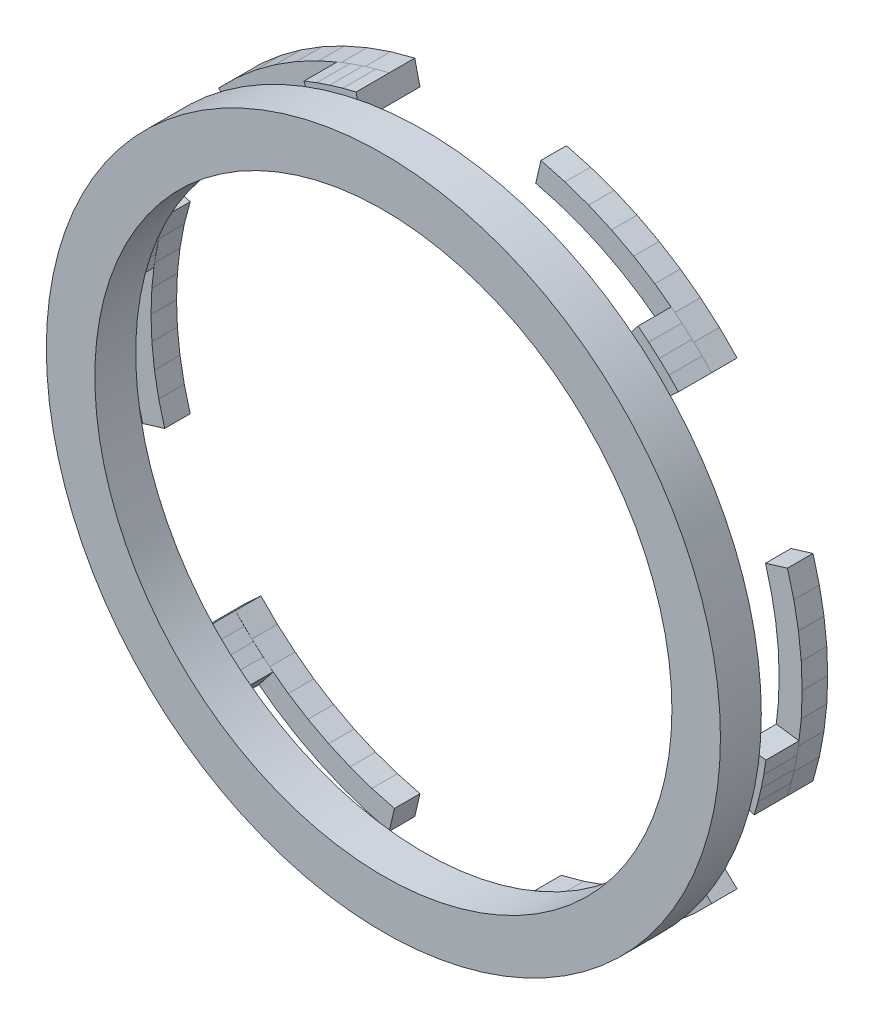
SolidWorks part; units mm, degrees
ref_plane "Front Plane" through (0, 0, 0) normal (0, 0, 1) x (1, 0, 0)
ref_plane "Top Plane" through (0, 0, 0) normal (0, 1, 0) x (1, 0, 0)
ref_plane "Right Plane" through (0, 0, 0) normal (1, 0, 0) x (0, 0, -1)
sketch "草圖1" plane through (0, 0, 0) normal (0, 0, 1) x (1, 0, 0)
  circle A0 centre (0, 0) radius 66
  circle A1 centre (0, 0) radius 56.5
extrude "填料-伸長1" add sketch "草圖1" along normal blind 8 from offset 13
sketch "草圖2" plane through (0, 0, 0) normal (0, 0, 1) x (1, 0, 0)
  line L0 (63.1161, -19.2965) -> (64.3726, -14.566)
  line L1 (64.3726, -14.566) -> (65.275, -9.7554)
  line L2 (65.275, -9.7554) -> (65.8185, -4.8912)
  line L3 (65.8185, -4.8912) -> (66, 0)
  line L4 (66, 0) -> (65.8185, 4.8912)
  line L5 (65.8185, 4.8912) -> (65.275, 9.7554)
  line L6 (65.275, 9.7554) -> (64.3726, 14.566)
  line L7 (64.3726, 14.566) -> (63.1161, 19.2965)
  line L8 (63.1161, 19.2965) -> (58.8127, 17.9809)
  line L9 (58.8127, 17.9809) -> (59.9836, 13.5729)
  line L10 (59.9836, 13.5729) -> (60.8245, 9.0903)
  line L11 (60.8245, 9.0903) -> (61.3309, 4.5577)
  line L12 (61.3309, 4.5577) -> (61.5, 0)
  line L13 (61.5, 0) -> (61.3309, -4.5577)
  line L14 (61.3309, -4.5577) -> (60.8245, -9.0903)
  line L15 (60.8245, -9.0903) -> (59.9836, -13.5729)
  line L16 (59.9836, -13.5729) -> (58.8127, -17.9809)
  line L17 (58.8127, -17.9809) -> (63.1161, -19.2965)
  line L18 (48.2693, 45.0119) -> (44.8008, 48.4653)
  line L19 (44.8008, 48.4653) -> (41.086, 51.6521)
  line L20 (41.086, 51.6521) -> (37.1451, 54.5549)
  line L21 (37.1451, 54.5549) -> (33, 57.1577)
  line L22 (33, 57.1577) -> (28.6734, 59.4461)
  line L23 (28.6734, 59.4461) -> (24.1891, 61.4076)
  line L24 (24.1891, 61.4076) -> (19.5717, 63.0313)
  line L25 (19.5717, 63.0313) -> (14.8468, 64.3084)
  line L26 (14.8468, 64.3084) -> (13.8345, 59.9238)
  line L27 (13.8345, 59.9238) -> (18.2373, 58.7337)
  line L28 (18.2373, 58.7337) -> (22.5398, 57.2207)
  line L29 (22.5398, 57.2207) -> (26.7184, 55.3929)
  line L30 (26.7184, 55.3929) -> (30.75, 53.2606)
  line L31 (30.75, 53.2606) -> (34.6125, 50.8353)
  line L32 (34.6125, 50.8353) -> (38.2847, 48.1304)
  line L33 (38.2847, 48.1304) -> (41.7462, 45.1608)
  line L34 (41.7462, 45.1608) -> (44.9783, 41.9429)
  line L35 (44.9783, 41.9429) -> (48.2693, 45.0119)
  line L36 (-14.8468, 64.3084) -> (-19.5717, 63.0313)
  line L37 (-19.5717, 63.0313) -> (-24.1891, 61.4076)
  line L38 (-24.1891, 61.4076) -> (-28.6734, 59.4461)
  line L39 (-28.6734, 59.4461) -> (-33, 57.1577)
  line L40 (-33, 57.1577) -> (-37.1451, 54.5549)
  line L41 (-37.1451, 54.5549) -> (-41.086, 51.6521)
  line L42 (-41.086, 51.6521) -> (-44.8008, 48.4653)
  line L43 (-44.8008, 48.4653) -> (-48.2693, 45.0119)
  line L44 (-48.2693, 45.0119) -> (-44.9783, 41.9429)
  line L45 (-44.9783, 41.9429) -> (-41.7462, 45.1608)
  line L46 (-41.7462, 45.1608) -> (-38.2847, 48.1304)
  line L47 (-38.2847, 48.1304) -> (-34.6125, 50.8353)
  line L48 (-34.6125, 50.8353) -> (-30.75, 53.2606)
  line L49 (-30.75, 53.2606) -> (-26.7184, 55.3929)
  line L50 (-26.7184, 55.3929) -> (-22.5398, 57.2207)
  line L51 (-22.5398, 57.2207) -> (-18.2373, 58.7337)
  line L52 (-18.2373, 58.7337) -> (-13.8345, 59.9238)
  line L53 (-13.8345, 59.9238) -> (-14.8468, 64.3084)
  line L54 (-63.1161, 19.2965) -> (-64.3726, 14.566)
  line L55 (-64.3726, 14.566) -> (-65.275, 9.7554)
  line L56 (-65.275, 9.7554) -> (-65.8185, 4.8912)
  line L57 (-65.8185, 4.8912) -> (-66, 0)
  line L58 (-66, 0) -> (-65.8185, -4.8912)
  line L59 (-65.8185, -4.8912) -> (-65.275, -9.7554)
  line L60 (-65.275, -9.7554) -> (-64.3726, -14.566)
  line L61 (-64.3726, -14.566) -> (-63.1161, -19.2965)
  line L62 (-63.1161, -19.2965) -> (-58.8127, -17.9809)
  line L63 (-58.8127, -17.9809) -> (-59.9836, -13.5729)
  line L64 (-59.9836, -13.5729) -> (-60.8245, -9.0903)
  line L65 (-60.8245, -9.0903) -> (-61.3309, -4.5577)
  line L66 (-61.3309, -4.5577) -> (-61.5, 0)
  line L67 (-61.5, 0) -> (-61.3309, 4.5577)
  line L68 (-61.3309, 4.5577) -> (-60.8245, 9.0903)
  line L69 (-60.8245, 9.0903) -> (-59.9836, 13.5729)
  line L70 (-59.9836, 13.5729) -> (-58.8127, 17.9809)
  line L71 (-58.8127, 17.9809) -> (-63.1161, 19.2965)
  line L72 (-48.2693, -45.0119) -> (-44.8008, -48.4653)
  line L73 (-44.8008, -48.4653) -> (-41.086, -51.6521)
  line L74 (-41.086, -51.6521) -> (-37.1451, -54.5549)
  line L75 (-37.1451, -54.5549) -> (-33, -57.1577)
  line L76 (-33, -57.1577) -> (-28.6734, -59.4461)
  line L77 (-28.6734, -59.4461) -> (-24.1891, -61.4076)
  line L78 (-24.1891, -61.4076) -> (-19.5717, -63.0313)
  line L79 (-19.5717, -63.0313) -> (-14.8468, -64.3084)
  line L80 (-14.8468, -64.3084) -> (-13.8345, -59.9238)
  line L81 (-13.8345, -59.9238) -> (-18.2373, -58.7337)
  line L82 (-18.2373, -58.7337) -> (-22.5398, -57.2207)
  line L83 (-22.5398, -57.2207) -> (-26.7184, -55.3929)
  line L84 (-26.7184, -55.3929) -> (-30.75, -53.2606)
  line L85 (-30.75, -53.2606) -> (-34.6125, -50.8353)
  line L86 (-34.6125, -50.8353) -> (-38.2847, -48.1304)
  line L87 (-38.2847, -48.1304) -> (-41.7462, -45.1608)
  line L88 (-41.7462, -45.1608) -> (-44.9783, -41.9429)
  line L89 (-44.9783, -41.9429) -> (-48.2693, -45.0119)
  line L90 (14.8468, -64.3084) -> (19.5717, -63.0313)
  line L91 (19.5717, -63.0313) -> (24.1891, -61.4076)
  line L92 (24.1891, -61.4076) -> (28.6734, -59.4461)
  line L93 (28.6734, -59.4461) -> (33, -57.1577)
  line L94 (33, -57.1577) -> (37.1451, -54.5549)
  line L95 (37.1451, -54.5549) -> (41.086, -51.6521)
  line L96 (41.086, -51.6521) -> (44.8008, -48.4653)
  line L97 (44.8008, -48.4653) -> (48.2693, -45.0119)
  line L98 (48.2693, -45.0119) -> (44.9783, -41.9429)
  line L99 (44.9783, -41.9429) -> (41.7462, -45.1608)
  line L100 (41.7462, -45.1608) -> (38.2847, -48.1304)
  line L101 (38.2847, -48.1304) -> (34.6125, -50.8353)
  line L102 (34.6125, -50.8353) -> (30.75, -53.2606)
  line L103 (30.75, -53.2606) -> (26.7184, -55.3929)
  line L104 (26.7184, -55.3929) -> (22.5398, -57.2207)
  line L105 (22.5398, -57.2207) -> (18.2373, -58.7337)
  line L106 (18.2373, -58.7337) -> (13.8345, -59.9238)
  line L107 (13.8345, -59.9238) -> (14.8468, -64.3084)
extrude "填料-伸長2" add sketch "草圖2" along normal blind 5
sketch "草圖3" plane through (0, 0, 0) normal (0, 0, 1) x (1, 0, 0)
  line L0 (63.1161, -19.2965) -> (63.847, -16.7202)
  line L1 (63.847, -16.7202) -> (64.4727, -14.1163)
  line L2 (64.4727, -14.1163) -> (64.9923, -11.4891)
  line L3 (64.9923, -11.4891) -> (65.4049, -8.8431)
  line L4 (65.4049, -8.8431) -> (60.9455, -8.2402)
  line L5 (60.9455, -8.2402) -> (60.561, -10.7058)
  line L6 (60.561, -10.7058) -> (60.0768, -13.1538)
  line L7 (60.0768, -13.1538) -> (59.4938, -15.5802)
  line L8 (59.4938, -15.5802) -> (58.8127, -17.9809)
  line L9 (58.8127, -17.9809) -> (63.1161, -19.2965)
  line L10 (48.2693, 45.0119) -> (46.4036, 46.933)
  line L11 (46.4036, 46.933) -> (44.4614, 48.7769)
  line L12 (44.4614, 48.7769) -> (42.446, 50.5404)
  line L13 (42.446, 50.5404) -> (40.3608, 52.2208)
  line L14 (40.3608, 52.2208) -> (37.6089, 48.6602)
  line L15 (37.6089, 48.6602) -> (39.552, 47.0945)
  line L16 (39.552, 47.0945) -> (41.4299, 45.4512)
  line L17 (41.4299, 45.4512) -> (43.2397, 43.733)
  line L18 (43.2397, 43.733) -> (44.9783, 41.9429)
  line L19 (44.9783, 41.9429) -> (48.2693, 45.0119)
  line L20 (-14.8468, 64.3084) -> (-17.4434, 63.6532)
  line L21 (-17.4434, 63.6532) -> (-20.0113, 62.8931)
  line L22 (-20.0113, 62.8931) -> (-22.5463, 62.0296)
  line L23 (-22.5463, 62.0296) -> (-25.0441, 61.0638)
  line L24 (-25.0441, 61.0638) -> (-23.3366, 56.9004)
  line L25 (-23.3366, 56.9004) -> (-21.009, 57.8003)
  line L26 (-21.009, 57.8003) -> (-18.6469, 58.605)
  line L27 (-18.6469, 58.605) -> (-16.2541, 59.3132)
  line L28 (-16.2541, 59.3132) -> (-13.8345, 59.9238)
  line L29 (-13.8345, 59.9238) -> (-14.8468, 64.3084)
  line L30 (-63.1161, 19.2965) -> (-63.847, 16.7202)
  line L31 (-63.847, 16.7202) -> (-64.4727, 14.1163)
  line L32 (-64.4727, 14.1163) -> (-64.9923, 11.4891)
  line L33 (-64.9923, 11.4891) -> (-65.4049, 8.8431)
  line L34 (-65.4049, 8.8431) -> (-60.9455, 8.2402)
  line L35 (-60.9455, 8.2402) -> (-60.561, 10.7058)
  line L36 (-60.561, 10.7058) -> (-60.0768, 13.1538)
  line L37 (-60.0768, 13.1538) -> (-59.4938, 15.5802)
  line L38 (-59.4938, 15.5802) -> (-58.8127, 17.9809)
  line L39 (-58.8127, 17.9809) -> (-63.1161, 19.2965)
  line L40 (-48.2693, -45.0119) -> (-46.4036, -46.933)
  line L41 (-46.4036, -46.933) -> (-44.4614, -48.7769)
  line L42 (-44.4614, -48.7769) -> (-42.446, -50.5404)
  line L43 (-42.446, -50.5404) -> (-40.3608, -52.2208)
  line L44 (-40.3608, -52.2208) -> (-37.6089, -48.6602)
  line L45 (-37.6089, -48.6602) -> (-39.552, -47.0945)
  line L46 (-39.552, -47.0945) -> (-41.4299, -45.4512)
  line L47 (-41.4299, -45.4512) -> (-43.2397, -43.733)
  line L48 (-43.2397, -43.733) -> (-44.9783, -41.9429)
  line L49 (-44.9783, -41.9429) -> (-48.2693, -45.0119)
  line L50 (14.8468, -64.3084) -> (17.4434, -63.6532)
  line L51 (17.4434, -63.6532) -> (20.0113, -62.8931)
  line L52 (20.0113, -62.8931) -> (22.5463, -62.0296)
  line L53 (22.5463, -62.0296) -> (25.0441, -61.0638)
  line L54 (25.0441, -61.0638) -> (23.3366, -56.9004)
  line L55 (23.3366, -56.9004) -> (21.009, -57.8003)
  line L56 (21.009, -57.8003) -> (18.6469, -58.605)
  line L57 (18.6469, -58.605) -> (16.2541, -59.3132)
  line L58 (16.2541, -59.3132) -> (13.8345, -59.9238)
  line L59 (13.8345, -59.9238) -> (14.8468, -64.3084)
extrude "填料-伸長3" add sketch "草圖3" along normal blind 6.5 from offset 5
